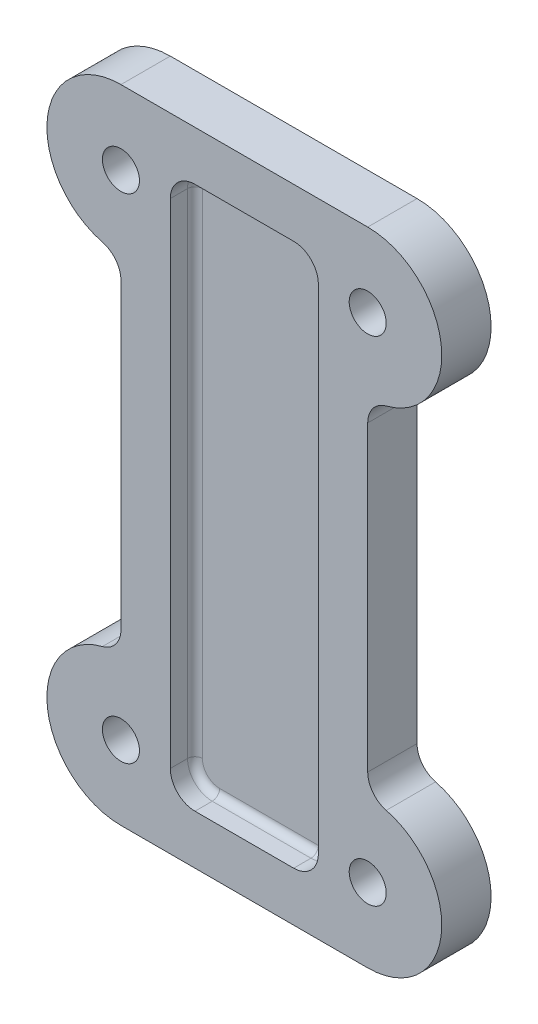
SolidWorks part; units mm, degrees
ref_plane "Front Plane" through (0, 0, 0) normal (0, 0, 1) x (1, 0, 0)
ref_plane "Top Plane" through (0, 0, 0) normal (0, 1, 0) x (1, 0, 0)
ref_plane "Right Plane" through (0, 0, 0) normal (1, 0, 0) x (0, 0, -1)
sketch "Sketch1" plane through (0, 0, 0) normal (0, 0, 1) x (1, 0, 0)
  line L0 (-15.875, 29.3688) -> (-15.875, 41.275)
  line L1 (15.875, -41.275) -> (-15.875, -41.275)
  line L2 (15.875, -41.275) -> (15.875, -29.3687)
  line L3 (15.875, 41.275) -> (-15.875, 41.275)
  line L4 (-15.875, -41.275) -> (-15.875, -29.3687)
  line L5 (15.875, -41.275) -> (-15.875, 41.275) construction
  line L6 (15.875, 41.275) -> (-15.875, -41.275) construction
  line L7 (15.875, 29.3687) -> (15.875, 41.275)
  line L8 (15.875, -19.4533) -> (15.875, 19.4533)
  line L9 (-15.875, -19.4533) -> (-15.875, 19.4533)
  circle A0 centre (-15.875, 31.75) radius 2.3812
  circle A1 centre (-15.875, -31.75) radius 2.3813
  circle A2 centre (15.875, 31.75) radius 2.3813
  circle A3 centre (15.875, -31.75) radius 2.3813
  arc A4 (-9.4923, 24.6799) -> (-18.2563, 22.5275) centre (-15.875, 31.75) ccw
  arc A5 (18.2563, 22.5275) -> (9.4923, 24.6799) centre (15.875, 31.75) ccw
  arc A6 (-18.2563, -22.5275) -> (-9.4923, -24.6799) centre (-15.875, -31.75) ccw
  arc A7 (9.4923, -24.6799) -> (18.2563, -22.5275) centre (15.875, -31.75) ccw
  arc A8 (18.2563, -22.5275) -> (15.875, -19.4533) centre (19.05, -19.4533) cw
  arc A9 (-18.2563, -22.5275) -> (-15.875, -19.4533) centre (-19.05, -19.4533) ccw
  arc A10 (18.2563, 22.5275) -> (15.875, 19.4533) centre (19.05, 19.4533) ccw
  arc A11 (-18.2563, 22.5275) -> (-15.875, 19.4533) centre (-19.05, 19.4533) cw
  point P0 (0, 0)
  point P28 (15.875, -22.225)
  point P31 (-15.875, -22.225)
  dimension "D2" = 4.7625
  dimension "D3" = 4.7625
  dimension "D4" = 4.7625
  dimension "D5" = 4.7625
  dimension "D9" = 3.175
  dimension "D1" = 31.75
  dimension "D6" = 31.75
  dimension "D7" = 9.525
  dimension "D8" = 31.75
extrude "Boss-Extrude1" add sketch "Sketch1" along normal blind 3.175
sketch "Sketch2" plane through (0, 0, 3.175) normal (0, 0, 1) x (1, 0, 0)
  line L0 (-15.875, -29.3687) -> (-15.875, -41.275)
  line L1 (-15.875, 41.275) -> (15.875, 41.275)
  line L2 (-15.875, 41.275) -> (-15.875, 29.3688)
  line L3 (-15.875, -41.275) -> (15.875, -41.275)
  line L4 (15.875, 41.275) -> (15.875, 29.3687)
  line L5 (-6.35, 34.925) -> (6.35, 34.925)
  line L6 (-9.525, 31.75) -> (-9.525, -31.75)
  line L7 (-6.35, -34.925) -> (6.35, -34.925)
  line L8 (9.525, 31.75) -> (9.525, -31.75)
  line L9 (-15.875, 19.4533) -> (-15.875, -19.4533)
  line L10 (15.875, 19.4533) -> (15.875, -19.4533)
  line L11 (15.875, -29.3688) -> (15.875, -41.275)
  circle A0 centre (-15.875, 31.75) radius 2.3812
  arc A1 (-6.8947, 34.925) -> (-18.2563, 22.5275) centre (-15.875, 31.75) ccw
  circle A2 centre (15.875, 31.75) radius 2.3813
  arc A3 (18.2563, 22.5275) -> (6.8947, 34.925) centre (15.875, 31.75) ccw
  circle A4 centre (15.875, -31.75) radius 2.3812
  arc A5 (6.8947, -34.925) -> (18.2563, -22.5275) centre (15.875, -31.75) ccw
  circle A6 centre (-15.875, -31.75) radius 2.3813
  arc A7 (-18.2563, -22.5275) -> (-6.8947, -34.925) centre (-15.875, -31.75) ccw
  arc A8 (-18.2563, 22.5275) -> (-15.875, 19.4533) centre (-19.05, 19.4533) cw
  arc A9 (15.875, 19.4533) -> (18.2563, 22.5275) centre (19.05, 19.4533) cw
  arc A10 (18.2563, -22.5275) -> (15.875, -19.4533) centre (19.05, -19.4533) cw
  arc A11 (-18.2563, -22.5275) -> (-15.875, -19.4533) centre (-19.05, -19.4533) ccw
  arc A12 (-6.35, -34.925) -> (-9.525, -31.75) centre (-6.35, -31.75) cw
  arc A13 (6.35, -34.925) -> (9.525, -31.75) centre (6.35, -31.75) ccw
  arc A14 (6.35, 34.925) -> (9.525, 31.75) centre (6.35, 31.75) cw
  arc A15 (-6.35, 34.925) -> (-9.525, 31.75) centre (-6.35, 31.75) ccw
  point P38 (-15.875, 22.225)
  dimension "D5" = 3.175
  dimension "D1" = 6.35
  dimension "D2" = 6.35
  dimension "D3" = 6.35
  dimension "D4" = 6.35
extrude "Boss-Extrude2" add sketch "Sketch2" along normal blind 3.175
fillet "Fillet1" radius 0.9525 8 edges at (0, 34.925, 3.175) (8.5951, 33.9951, 3.175) (9.525, 0, 3.175) (8.5951, -33.9951, 3.175) (0, -34.925, 3.175) (-8.5951, -33.9951, 3.175) (-9.525, 0, 3.175) (-8.5951, 33.9951, 3.175)
